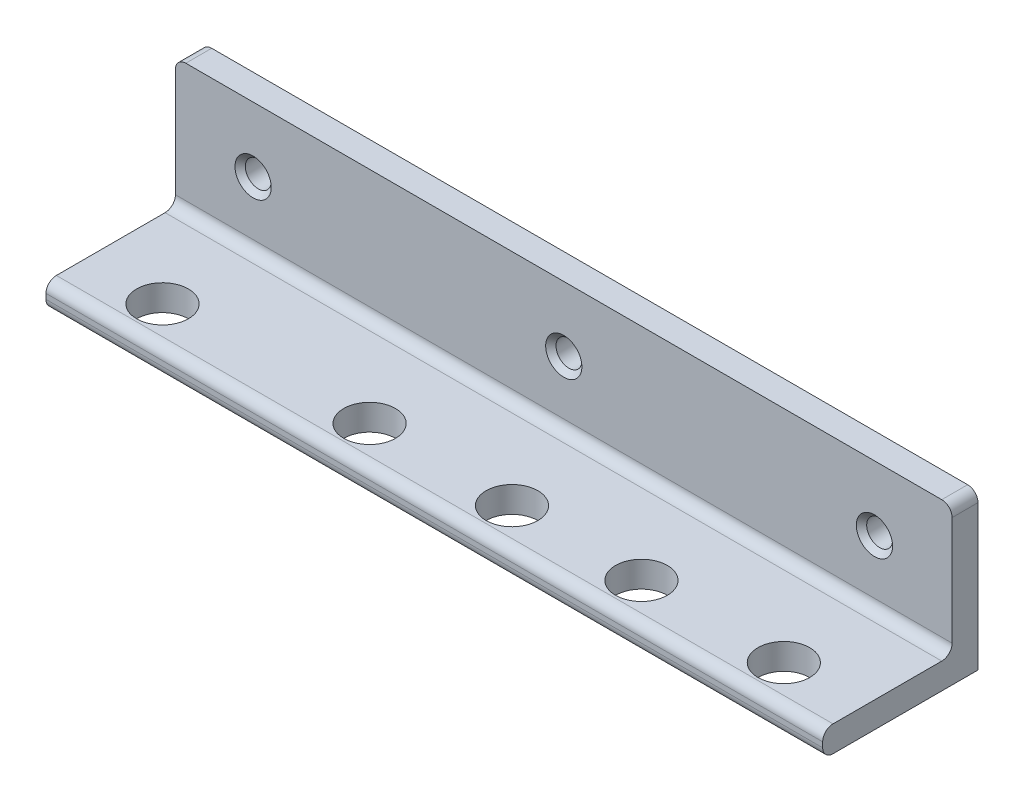
SolidWorks part; units mm, degrees
ref_plane "Front Plane" through (0, 0, 0) normal (0, 0, 1) x (1, 0, 0)
ref_plane "Top Plane" through (0, 0, 0) normal (0, 1, 0) x (1, 0, 0)
ref_plane "Right Plane" through (0, 0, 0) normal (1, 0, 0) x (0, 0, -1)
sketch "Sketch1" plane through (0, 0, 0) normal (0, 1, 0) x (1, 0, 0)
  line L1 (-52.6912, -15.8157) -> (97.3088, -15.8157)
  line L2 (-52.6912, -15.8157) -> (-52.6912, 14.1843)
  line L3 (-52.6912, 14.1843) -> (97.3088, 14.1843)
  line L4 (97.3088, -15.8157) -> (97.3088, 14.1843)
  dimension "D1" = 30
  dimension "D2" = 150
extrude "Boss-Extrude1" add sketch "Sketch1" along normal blind 5
sketch "Sketch3" plane through (0, 5, 0) normal (0, 1, 0) x (1, 0, 0)
  line L0 (97.3088, 14.1843) -> (-52.6912, 14.1843) construction
  line L1 (-52.6912, 14.1843) -> (97.3088, 14.1843)
  line L2 (-52.6912, 14.1843) -> (-52.6912, 9.1843)
  line L3 (-52.6912, 9.1843) -> (97.3088, 9.1843)
  line L4 (97.3088, 14.1843) -> (97.3088, 9.1843)
  line L5 (97.3088, -15.8157) -> (97.3088, 14.1843) construction
  dimension "D1" = 5
  dimension "D2" = 150
extrude "Boss-Extrude2" add sketch "Sketch3" along normal blind 25
ref_plane "Plane1" through (-52.6912, 0, 15.8157) normal (1, 0, 0) x (0, 0, -1)
sketch "Sketch6" plane through (0, 5, 0) normal (0, 1, 0) x (1, 0, 0)
  circle A5 centre (82.3088, -8.3157) radius 5
  circle A6 centre (54.8088, -8.3157) radius 5
  circle A7 centre (29.8088, -8.3157) radius 5
  circle A8 centre (2.3088, -8.3157) radius 5
  circle A9 centre (-37.6912, -8.3157) radius 5
extrude "Cut-Extrude2" cut sketch "Sketch6" against normal blind 25
sketch "Sketch7" plane through (0, 0, -9.1843) normal (0, 0, 1) x (1, 0, 0)
  line L0 (97.3088, 30) -> (97.3088, 5) construction
  line L1 (-52.6912, 30) -> (-52.6912, 5) construction
  circle A0 centre (82.3088, 17.4787) radius 2.5
  circle A1 centre (-37.6912, 17.4787) radius 2.5
  circle A2 centre (22.3088, 17.4787) radius 2.5
  point P2 (97.3088, 17.5)
  dimension "D1" = 15
  dimension "D2" = 15
extrude "Cut-Extrude3" cut sketch "Sketch7" against normal blind 25
chamfer "Chamfer1" distance 1 angle 45 3 edges at (24.8088, 17.4787, -9.1843) (-35.1912, 17.4787, -9.1843) (84.8088, 17.4787, -9.1843)
fillet "Fillet2" radius 2 5 edges at (22.3088, 5, 15.8157) (22.3088, 0, 15.8157) (-52.6912, 30, -11.6843) (97.3088, 30, -11.6843)
